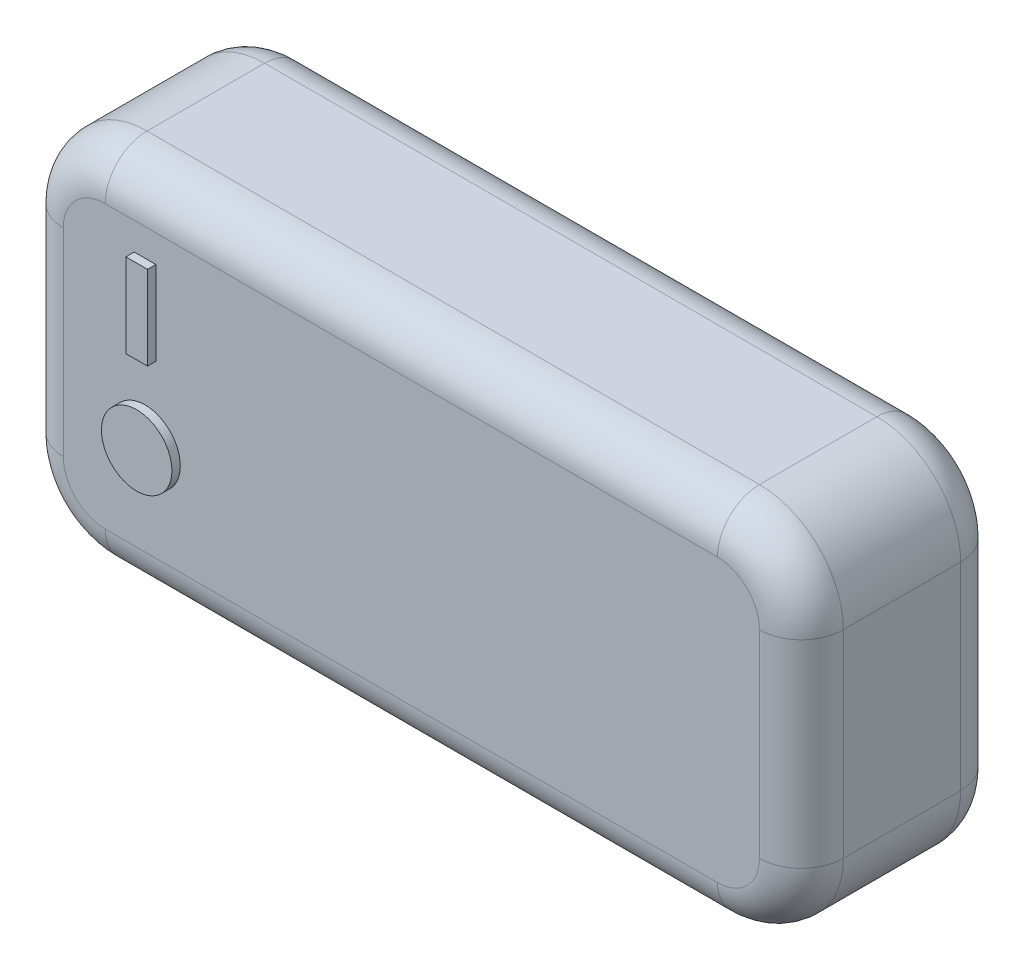
SolidWorks part; units mm, degrees
ref_plane "Alzado" through (0, 0, 0) normal (0, 0, 1) x (1, 0, 0)
ref_plane "Planta" through (0, 0, 0) normal (0, 1, 0) x (1, 0, 0)
ref_plane "Vista lateral" through (0, 0, 0) normal (1, 0, 0) x (0, 0, -1)
sketch "Croquis1" plane through (0, 0, 0) normal (0, 0, 1) x (1, 0, 0)
  line L1 (-46.5, 21.8) -> (46.5, 21.8)
  line L2 (-46.5, 21.8) -> (-46.5, -21.8)
  line L3 (-46.5, -21.8) -> (46.5, -21.8)
  line L4 (46.5, 21.8) -> (46.5, -21.8)
  line L5 (-46.5, 21.8) -> (46.5, -21.8) construction
  line L6 (-46.5, -21.8) -> (46.5, 21.8) construction
  point P0 (0, 0)
  dimension "D1" = 43.6
  dimension "D2" = 93
extrude "Saliente-Extruir1" add sketch "Croquis1" along normal blind 24
fillet "Redondeo1" radius 10 4 edges at (46.5, -21.8, 12) (46.5, 21.8, 12) (-46.5, -21.8, 12) (-46.5, 21.8, 12)
fillet "Redondeo2" radius 5 16 edges at (43.5711, 18.8711, 0) (0, 21.8, 0) (-43.5711, 18.8711, 0) (-46.5, 0, 0) (-43.5711, -18.8711, 0) (0, -21.8, 0) (43.5711, -18.8711, 0) (46.5, 0, 0) (-43.5711, -18.8711, 24) (-46.5, 0, 24) (-43.5711, 18.8711, 24) (0, 21.8, 24) (43.5711, 18.8711, 24) (46.5, 0, 24) (43.5711, -18.8711, 24) (0, -21.8, 24)
sketch "Croquis2" plane through (-46.5, 0, 0) normal (-1, 0, 0) x (0, 0, 1)
  line L0 (5, -11.8) -> (19, -11.8) construction
  line L1 (9.3669, -2.4851) -> (14.6331, -2.4851)
  line L2 (9.3669, -2.4851) -> (9.3669, -11.8)
  line L3 (9.3669, -11.8) -> (14.6331, -11.8)
  line L4 (14.6331, -2.4851) -> (14.6331, -11.8)
  line L5 (9.3669, -2.4851) -> (14.6331, -11.8) construction
  line L6 (9.3669, -11.8) -> (14.6331, -2.4851) construction
  line L7 (12, -7.1426) -> (12, -11.8) construction
  line L8 (12, -7.1426) -> (12, 2.7922) construction
  line L9 (12, 2.7922) -> (12, 7.9846) construction
  line L11 (11.1097, 4.7391) -> (12.8903, 4.7391)
  line L12 (11.1097, 4.7391) -> (11.1097, 0.8454)
  line L13 (11.1097, 0.8454) -> (12.8903, 0.8454)
  line L14 (12.8903, 4.7391) -> (12.8903, 0.8454)
  line L15 (11.1097, 4.7391) -> (12.8903, 0.8454) construction
  line L16 (11.1097, 0.8454) -> (12.8903, 4.7391) construction
  circle A0 centre (12, 7.9846) radius 1.7953
  point P0 (12, -7.1426)
extrude "Cortar-Extruir1" cut sketch "Croquis2" against normal blind 10
sketch "Croquis4" plane through (0, 0, 24) normal (0, 0, 1) x (1, 0, 0)
  line L0 (-31.7478, 8.5413) -> (-31.7478, -5.8016) construction
  line L1 (-33.037, 13.5371) -> (-30.4585, 13.5371)
  line L2 (-33.037, 13.5371) -> (-33.037, 3.5454)
  line L3 (-33.037, 3.5454) -> (-30.4585, 3.5454)
  line L4 (-30.4585, 13.5371) -> (-30.4585, 3.5454)
  line L5 (-33.037, 13.5371) -> (-30.4585, 3.5454) construction
  line L6 (-33.037, 3.5454) -> (-30.4585, 13.5371) construction
  circle A0 centre (-31.7478, -5.8016) radius 4.2024
  point P2 (-31.7478, 8.5413)
extrude "Saliente-Extruir2" add sketch "Croquis4" along normal blind 1
